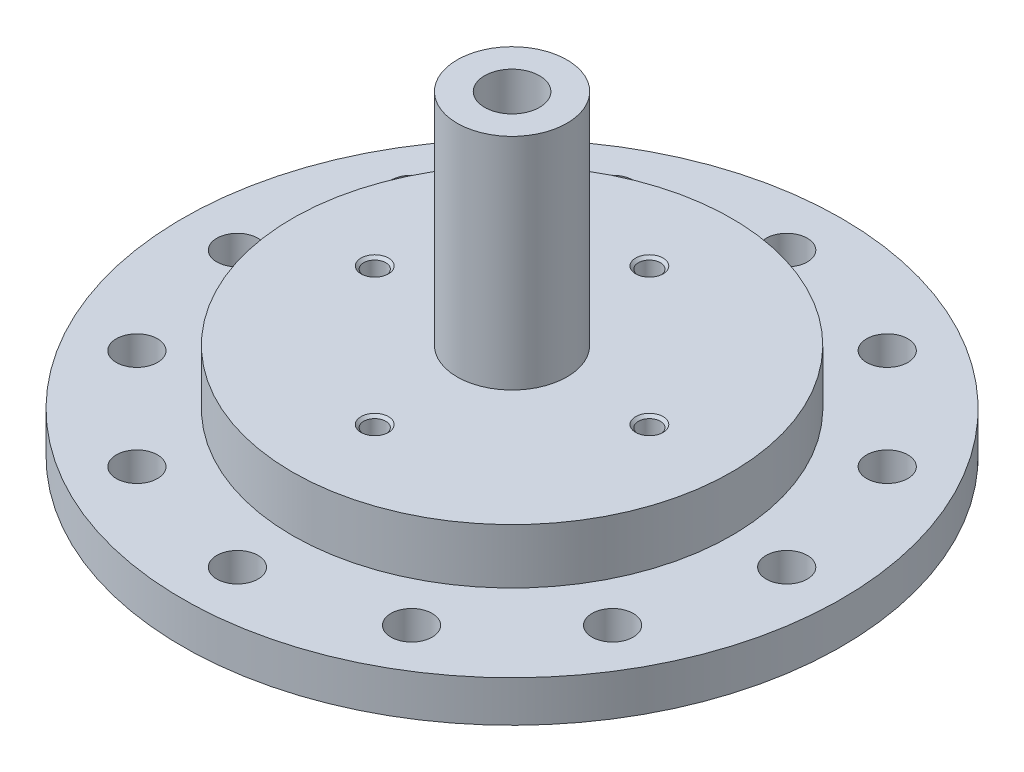
SolidWorks part; units mm, degrees
other "DetailItem8"
other "DetailItem9"
ref_plane "Front Plane" through (0, 0, 0) normal (0, 0, 1) x (1, 0, 0)
ref_plane "Top Plane" through (0, 0, 0) normal (0, 1, 0) x (1, 0, 0)
ref_plane "Right Plane" through (0, 0, 0) normal (1, 0, 0) x (0, 0, -1)
sketch "Sketch1" plane through (0, 0, 0) normal (0, 0, 1) x (1, 0, 0)
  line L0 (76.2, 9.525) -> (0, 9.525)
  line L1 (0, 9.525) -> (0, 0)
  line L2 (0, 0) -> (76.2, 0)
  line L3 (76.2, 0) -> (76.2, 9.525)
  line L4 (0, 9.525) -> (0, 0) construction
revolve "Revolve1" add sketch "Sketch1" angle 360 about L4
sketch "Sketch2" plane through (0, 9.525, 0) normal (0, 1, 0) x (-1, 0, 0)
  circle A0 centre (0, 0) radius 50.8
extrude "Boss-Extrude1" add sketch "Sketch2" along normal blind 12.7
sketch "Sketch3" plane through (0, 22.225, 0) normal (0, 1, 0) x (-1, 0, 0)
  circle A0 centre (0, 0) radius 12.7
extrude "Boss-Extrude2" add sketch "Sketch3" along normal blind 50.8
hole_wizard "3/8 (0.375) Diameter Hole1" positions "Sketch5" profile "Sketch4" hole size "3/8" standard "ANSI Inch"
sketch "Sketch5" plane through (0, 9.525, 0) normal (0, 1, 0) x (1, 0, 0)
  point P0 (63.5, 0)
  point P1 (54.9926, 31.75)
  point P2 (31.75, 54.9926)
  point P3 (0, -63.5)
  point P4 (-31.75, -54.9926)
  point P5 (-54.9926, -31.75)
  point P6 (-63.5, 0)
  point P7 (-54.9926, 31.75)
  point P8 (-31.75, 54.9926)
  point P9 (0, 63.5)
  point P10 (31.75, -54.9926)
  point P11 (54.9926, -31.75)
sketch "Sketch4" plane through (63.5, 9.525, 0) normal (1, 0, 0) x (0, 0, 1)
  line L0 (0, 0) -> (0, 9.525)
  line L1 (0, 9.525) -> (4.7625, 9.525)
  line L2 (4.7625, 9.525) -> (4.7625, 0)
  line L5 (4.7625, 0) -> (0, 0)
  line L11 (0, -6.35) -> (0, 107.95) construction
  dimension "Thru Hole Dia." = 9.525
  dimension "Thru Hole Depth" = 9.525
hole_wizard "2-4.5 Tapped Hole1" positions "Sketch7" profile "Sketch6" tap size "2-4.5" standard "ANSI Inch"
sketch "Sketch7" plane through (0, 0, 0) normal (0, -1, 0) x (-1, 0, 0)
  point P0 (0, 0)
sketch "Sketch6" plane through (0, 0, 0) normal (1, 0, 0) x (0, 0, -1)
  line L0 (0, 0) -> (0, 73.025)
  line L1 (0, 73.025) -> (6.35, 73.025)
  line L3 (6.35, 73.025) -> (6.35, 3.175)
  line L4 (6.35, 3.175) -> (25.4, 3.175)
  line L5 (25.4, 3.175) -> (25.4, 0)
  line L7 (25.4, 0) -> (0, 0)
  line L11 (0, -6.35) -> (0, 107.95) construction
  dimension "Thru Tap Drill Dia." = 12.7
  dimension "Thru Tap Drill Depth" = 73.025
  dimension "Thread Major Dia." = 50.8
  dimension "Thread Depth" = 3.175
hole_wizard "#7 (0.201) Diameter Hole1" positions "Sketch9" profile "Sketch8" hole size "#7" standard "ANSI Inch"
sketch "Sketch9" plane through (0, 22.225, 0) normal (0, 1, 0) x (1, 0, 0)
  point P0 (31.75, 0)
  point P1 (0, -31.75)
  point P2 (0, 31.75)
  point P3 (-31.75, 0)
sketch "Sketch8" plane through (31.75, 22.225, 0) normal (1, 0, 0) x (0, 0, 1)
  line L0 (0, 0) -> (0, 14.2338)
  line L1 (0, 14.2338) -> (2.5527, 12.7)
  line L2 (2.5527, 12.7) -> (2.5527, 0)
  line L5 (2.5527, 0) -> (0, 0)
  line L10 (0, 14.2338) -> (-2.5527, 12.7) construction
  line L11 (0, -6.35) -> (0, 107.95) construction
  dimension "Hole Dia." = 5.1054
  dimension "Hole Depth" = 12.7
  dimension "Drill Angle" = 118
chamfer "Chamfer1" distance 0.6223 angle 45 4 edges at (-31.75, 22.225, 2.5527) (0, 22.225, -29.1973) (31.75, 22.225, 2.5527) (0, 22.225, 34.3027)
